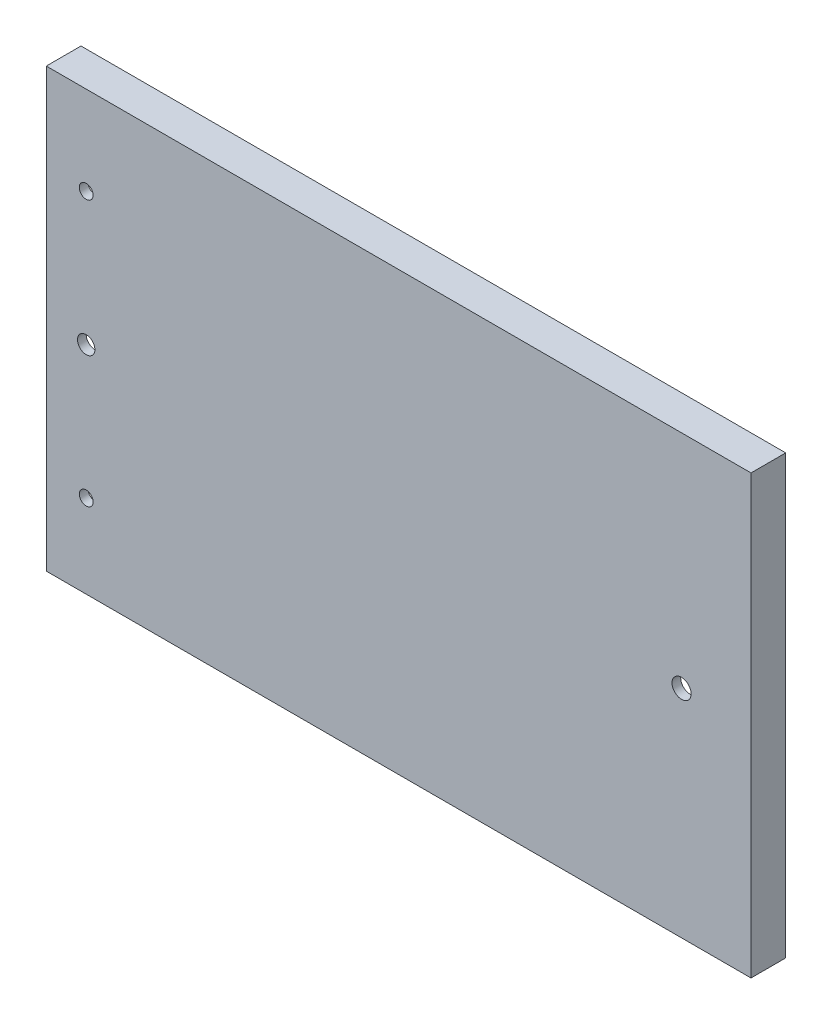
SolidWorks part; units mm, degrees
material "Настроенная пользователем пластмасса"
ref_plane "Спереди" through (0, 0, 0) normal (0, 0, 1) x (1, 0, 0)
ref_plane "Сверху" through (0, 0, 0) normal (0, 1, 0) x (1, 0, 0)
ref_plane "Справа" through (0, 0, 0) normal (1, 0, 0) x (0, 0, -1)
ref_plane "Плоскость4" through (0, 0, 0) normal (0, 0, -1) x (-1, 0, 0)
sketch "Эскиз1" plane through (0, 0, 0) normal (0, 0, -1) x (-1, 0, 0)
  line L0 (0, 252) -> (-406, 252)
  line L1 (-406, 252) -> (-406, 0)
  line L2 (-406, 0) -> (0, 0)
  line L3 (0, 0) -> (0, 252)
extrude "Бобышка-Вытянуть1" add sketch "Эскиз1" against normal blind 20
sketch "Эскиз2" plane through (0, 0, 0) normal (0, 0, -1) x (-1, 0, 0)
  line L0 (-388, 241) -> (-388, 8)
  line L1 (-388, 8) -> (-3, 8)
  line L2 (-3, 8) -> (-3, 241)
  line L3 (-3, 241) -> (-388, 241)
extrude "Вырез-Вытянуть1" cut sketch "Эскиз2" against normal blind 15
hole_wizard "Диаметр отверстия Ø10.0 (10)1" positions "Эскиз4" profile "Эскиз3" hole size "Ø10.0" standard "Ansi Metric"
sketch "Эскиз4" plane through (0, 0, 15) normal (0, 0, -1) x (-1, 0, 0)
  point P0 (-23, 124.5)
sketch "Эскиз3" plane through (23, 124.5, 15) normal (1, 0, 0) x (0, 1, 0)
  line L0 (0, 0) -> (0, 5)
  line L1 (0, 5) -> (5, 5)
  line L2 (5, 5) -> (5, 0)
  line L5 (5, 0) -> (0, 0)
  line L11 (0, -6.35) -> (0, 107.95) construction
  dimension "Диаметр сквозного отверстия" = 10
  dimension "Глубина сквозного отверстия" = 5
hole_wizard "Диаметр отверстия Ø8.0 (8)1" positions "Эскиз6" profile "Эскиз5" hole size "Ø8.0" standard "Ansi Metric"
sketch "Эскиз6" plane through (0, 0, 15) normal (0, 0, -1) x (-1, 0, 0)
  point P0 (-23, 201)
  point P1 (-23, 48)
sketch "Эскиз5" plane through (23, 201, 15) normal (1, 0, 0) x (0, 1, 0)
  line L0 (0, 0) -> (0, 5)
  line L1 (0, 5) -> (4, 5)
  line L2 (4, 5) -> (4, 0)
  line L5 (4, 0) -> (0, 0)
  line L11 (0, -6.35) -> (0, 107.95) construction
  dimension "Диаметр сквозного отверстия" = 8
  dimension "Глубина сквозного отверстия" = 5
hole_wizard "Диаметр отверстия Ø11.0 (11)1" positions "Эскиз8" profile "Эскиз7" hole size "Ø11.0" standard "Ansi Metric"
sketch "Эскиз8" plane through (0, 0, 15) normal (0, 0, -1) x (-1, 0, 0)
  point P0 (-366, 124.5)
sketch "Эскиз7" plane through (366, 124.5, 15) normal (1, 0, 0) x (0, 1, 0)
  line L0 (0, 0) -> (0, 5)
  line L1 (0, 5) -> (5.5, 5)
  line L2 (5.5, 5) -> (5.5, 0)
  line L5 (5.5, 0) -> (0, 0)
  line L11 (0, -6.35) -> (0, 107.95) construction
  dimension "Диаметр сквозного отверстия" = 11
  dimension "Глубина сквозного отверстия" = 5
